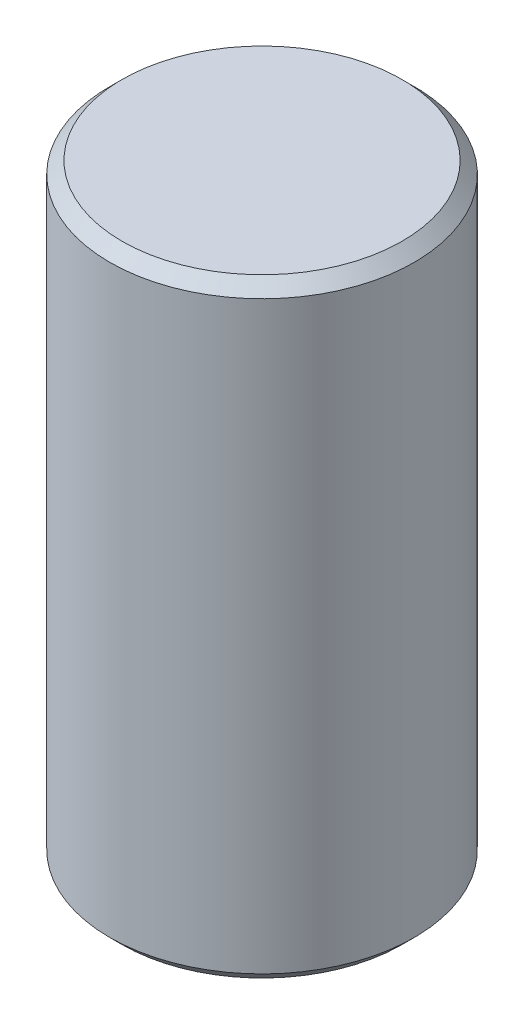
SolidWorks part; units mm, degrees
ref_plane "Front Plane" through (0, 0, 0) normal (0, 0, 1) x (1, 0, 0)
ref_plane "Top Plane" through (0, 0, 0) normal (0, 1, 0) x (1, 0, 0)
ref_plane "Right Plane" through (0, 0, 0) normal (1, 0, 0) x (0, 0, -1)
sketch "Sketch1" plane through (0, 0, 0) normal (0, 1, 0) x (1, 0, 0)
  circle A0 centre (0, 0) radius 1.25
extrude "Boss-Extrude1" add sketch "Sketch1" along normal mid plane 5
chamfer "Chamfer1" distance 0.1 angle 45 2 edges at (0, -2.5, 1.25) (0, 2.5, 1.25)
